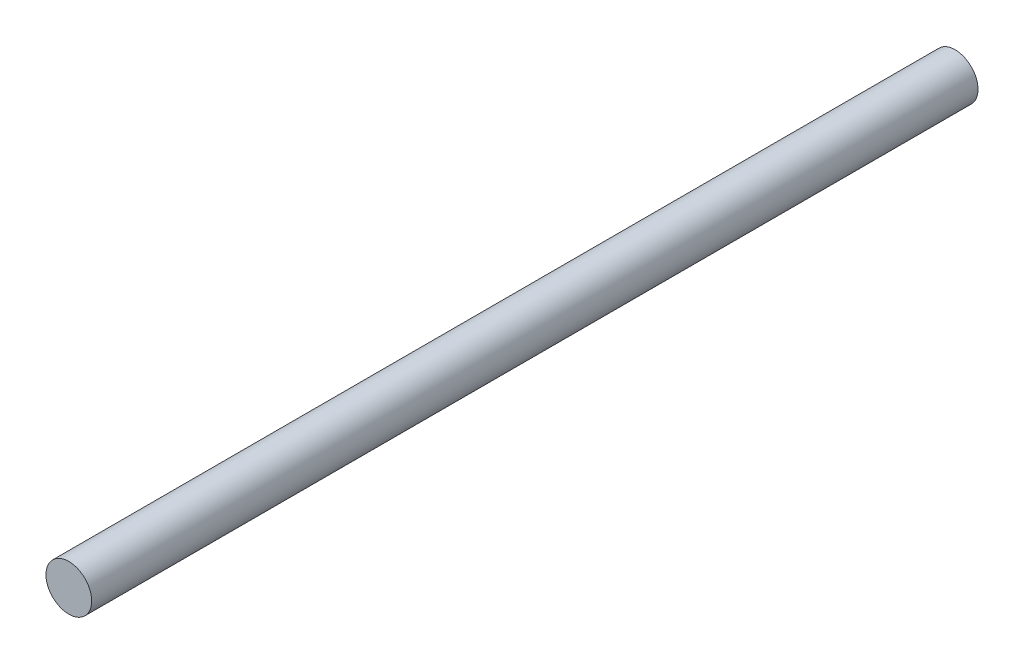
SolidWorks part; units mm, degrees
ref_plane "Front" through (0, 0, 0) normal (0, 0, 1) x (1, 0, 0)
ref_plane "Top" through (0, 0, 0) normal (0, 1, 0) x (1, 0, 0)
ref_plane "Right" through (0, 0, 0) normal (1, 0, 0) x (0, 0, -1)
sketch "Sketch1" plane through (0, 0, 0) normal (0, 0, 1) x (1, 0, 0)
  circle A0 centre (0, 0) radius 3.95
  dimension "D1" = 7.9
extrude "Boss-Extrude1" add sketch "Sketch1" along normal blind 153.15
equation "\"rod_length_zaxis\"=153.15"
equation "\"D1@Boss-Extrude1\"=\"rod_length_zaxis\""
